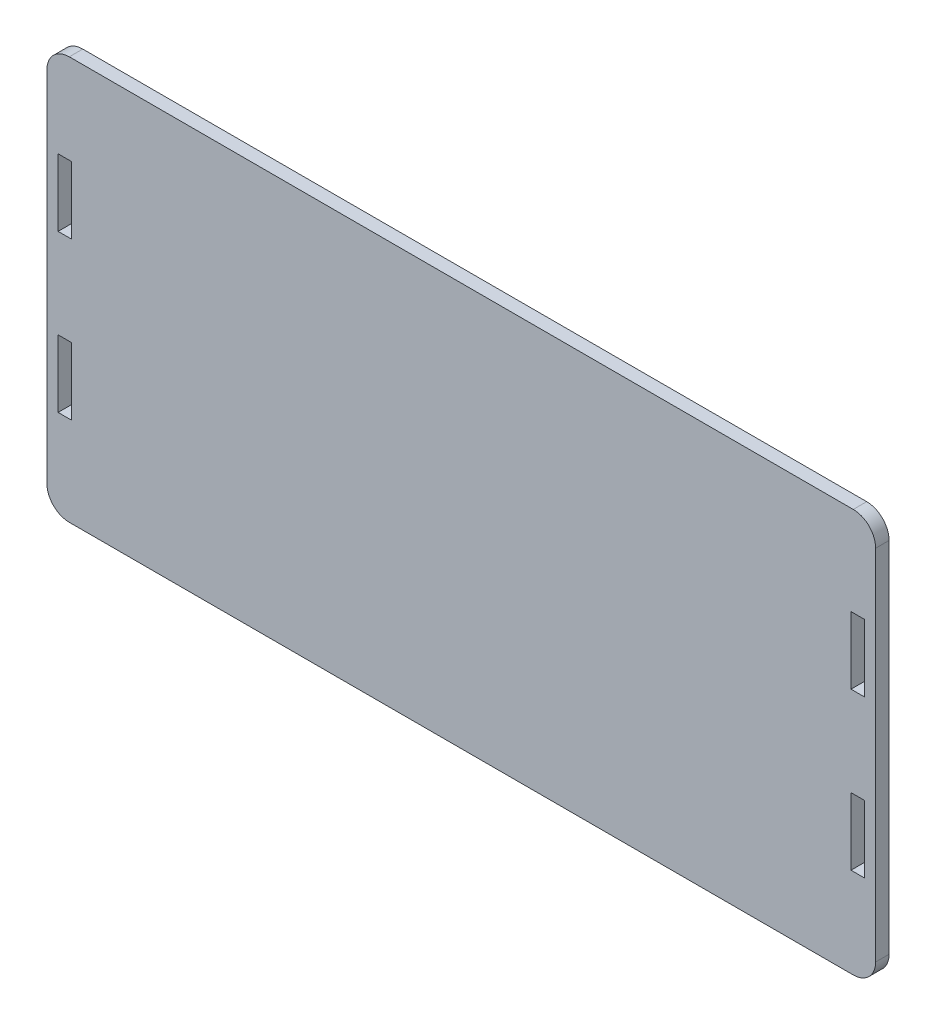
SolidWorks part; units mm, degrees
ref_plane "Plan de face" through (0, 0, 0) normal (0, 0, 1) x (1, 0, 0)
ref_plane "Plan de dessus" through (0, 0, 0) normal (0, 1, 0) x (1, 0, 0)
ref_plane "Plan de droite" through (0, 0, 0) normal (1, 0, 0) x (0, 0, -1)
sketch "Esquisse1" plane through (0, 0, 0) normal (0, 0, 1) x (1, 0, 0)
  line L1 (0, 0) -> (370, 0)
  line L2 (0, 0) -> (0, 180)
  line L3 (0, 180) -> (370, 180)
  line L4 (370, 0) -> (370, 180)
  dimension "D1" = 180
  dimension "D2" = 370
extrude "Boss.-Extru.1" add sketch "Esquisse1" along normal blind 6
sketch "Esquisse2" plane through (0, 0, 6) normal (0, 0, 1) x (1, 0, 0)
  line L0 (370, 180) -> (0, 180) construction
  line L1 (5, 40) -> (11, 40)
  line L2 (5, 40) -> (5, 70)
  line L3 (5, 70) -> (11, 70)
  line L4 (11, 40) -> (11, 70)
  line L5 (11, 110) -> (5, 110)
  line L6 (11, 110) -> (11, 140)
  line L7 (11, 140) -> (5, 140)
  line L8 (5, 110) -> (5, 140)
  line L9 (0, 0) -> (370, 0) construction
  line L10 (0, 180) -> (0, 0) construction
  line L11 (185, 180) -> (185, 0) construction
  line L12 (365, 110) -> (365, 140)
  line L13 (359, 140) -> (365, 140)
  line L14 (359, 110) -> (359, 140)
  line L15 (359, 110) -> (365, 110)
  line L16 (359, 40) -> (359, 70)
  line L17 (365, 70) -> (359, 70)
  line L18 (365, 40) -> (365, 70)
  line L19 (365, 40) -> (359, 40)
  dimension "D1" = 30
  dimension "D2" = 6
  dimension "D3" = 30
  dimension "D4" = 6
  dimension "D5" = 40
  dimension "D6" = 40
  dimension "D7" = 5
  dimension "D8" = 5
extrude "Enlèv. mat.-Extru.1" cut sketch "Esquisse2" against normal blind 10
fillet "Congé1" radius 10 4 edges at (0, 180, 3) (0, 0, 3) (370, 180, 3) (370, 0, 3)
